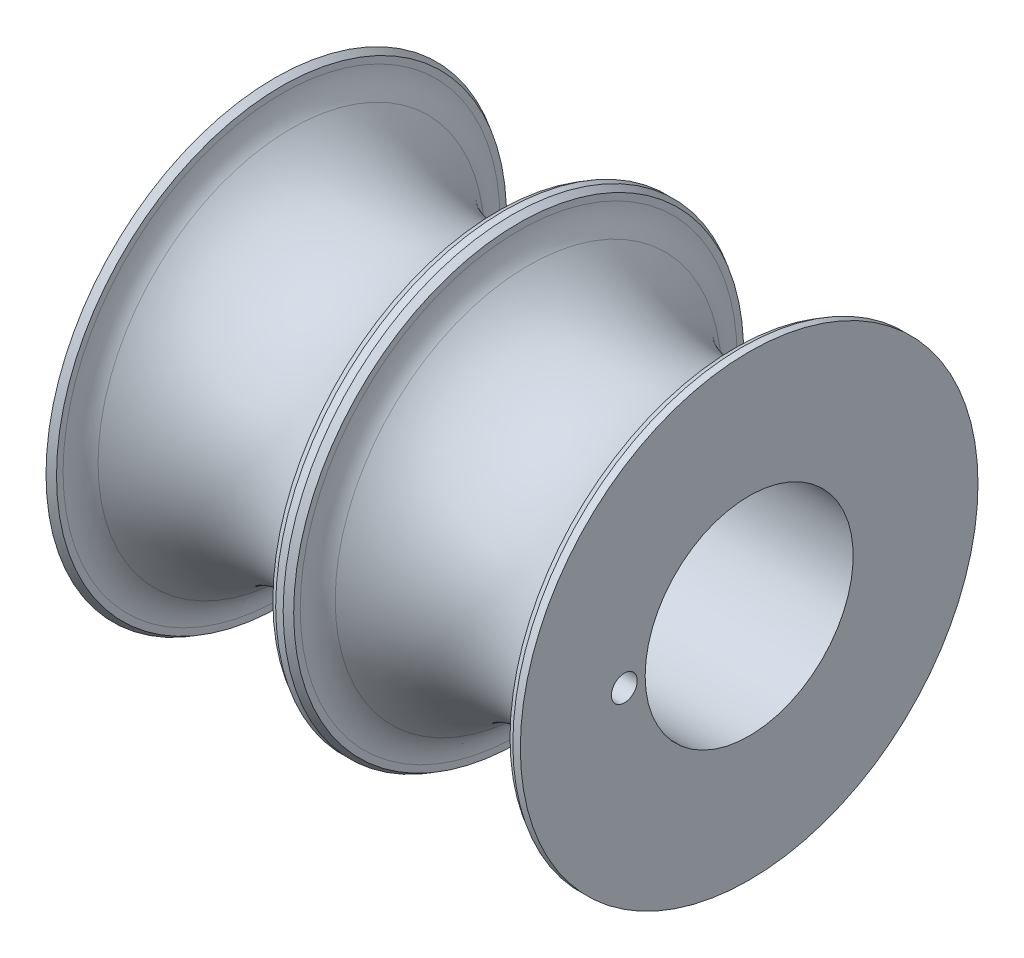
SolidWorks part; units mm, degrees
other "Detailelement1"
other "Detailelement2"
other "Detailelement3"
other "Detailelement4"
other "Detailelement5"
material "1.7131 (16MnCr5)"
ref_plane "Vorne" through (0, 0, 0) normal (0, 0, 1) x (1, 0, 0)
ref_plane "Oben" through (0, 0, 0) normal (0, 1, 0) x (1, 0, 0)
ref_plane "Rechts" through (0, 0, 0) normal (1, 0, 0) x (0, 0, -1)
ref_axis "Achse1" through (-27.8308, 0, 0) along (1, 0, 0)
sketch "Skizze1" plane through (0, 0, 0) normal (0, 0, 1) x (1, 0, 0)
  line L0 (0, 12.5) -> (57, 12.5)
  line L1 (26.8, 27.0381) -> (27.6, 27.5)
  line L2 (55.3, 27.0381) -> (56.1, 27.5)
  line L3 (29.3, 26.25) -> (29.3, 27.0381)
  line L4 (-27.8308, 0) -> (70.0749, 0) construction
  line L5 (13.8, 29.3523) -> (13.8, 13.5957) construction
  line L6 (0, 27.5) -> (0.8, 27.0381)
  line L7 (0, 27.5) -> (0, 12.5)
  line L8 (0.8, 26.25) -> (0.8, 27.0381)
  line L9 (26.8, 26.25) -> (26.8, 27.0381)
  line L10 (27.6, 27.5) -> (28.5, 27.5)
  line L11 (0, 0) -> (107.1415, 0) construction
  line L12 (28.5, 27.5) -> (29.3, 27.0381)
  line L17 (55.3, 26.25) -> (55.3, 27.0381)
  line L19 (56.1, 27.5) -> (57, 27.5)
  line L20 (57, 27.5) -> (57, 12.5)
  line L21 (42.3, 33.996) -> (42.3, 13.5957) construction
  arc A0 (41.9408, 18) -> (54.1261, 23.219) centre (42.3, 33.996) ccw
  arc A1 (55.3, 26.25) -> (54.1261, 23.219) centre (50.8, 26.25) cw
  arc A2 (29.3, 26.25) -> (30.4739, 23.219) centre (33.8, 26.25) ccw
  arc A3 (41.9408, 18) -> (30.4739, 23.219) centre (42.3, 33.996) cw
  arc A4 (0.8, 26.25) -> (1.9739, 23.219) centre (5.3, 26.25) ccw
  arc A5 (13.4408, 18) -> (1.9739, 23.219) centre (13.8, 33.996) cw
  arc A6 (13.4408, 18) -> (25.6261, 23.219) centre (13.8, 33.996) ccw
  arc A7 (26.8, 26.25) -> (25.6261, 23.219) centre (22.3, 26.25) cw
  dimension "D3" = 26
  dimension "D4" = 4.5
  dimension "D10" = 55
  dimension "D11" = 0.9
  dimension "D5" = 16
  dimension "D1" = 2
  dimension "D2" = 28.5
  dimension "D6" = 25
  dimension "D7" = 57
  dimension "D8" = 8.25
  dimension "D9" = 36
  dimension "D12" = 2.5
  dimension "D13" = 0.8
  dimension "D14" = 30
  dimension "D15" = 0.8
revolve "Rotation2" add sketch "Skizze1" angle 360 about axis through (-27.8308, 0, 0) along (1, 0, 0)
hole_wizard "Ø3.0 (3) Durchmesser Bohrung2" positions "Skizze6" profile "Skizze5" hole size "Ø3.0" standard "Gabler-Normteile"
sketch "Skizze6" plane through (0, 0, 0) normal (-1, 0, 0) x (0, 0, 1)
  point P0 (-15, 0)
  dimension "D2" = 15
sketch "Skizze5" plane through (0, 0, -15) normal (0, 1, 0) x (0, 0, 1)
  line L0 (0, 0) -> (0, 5.9013)
  line L1 (0, 5.9013) -> (1.5, 5)
  line L2 (1.5, 5) -> (1.5, 0)
  line L5 (1.5, 0) -> (0, 0)
  line L10 (0, 5.9013) -> (-1.5, 5) construction
  line L11 (0, -6.35) -> (0, 107.95) construction
  dimension "Bohrerdurchmesser" = 3
  dimension "Bohrungstiefe" = 5
  dimension "Spitzenwinkel" = 118
hole_wizard "Ø3.1 (3.1) Durchmesser Bohrung2" positions "Skizze8" profile "Skizze7" hole size "Ø3.1" standard "Gabler-Normteile"
sketch "Skizze8" plane through (57, 0, 0) normal (1, 0, 0) x (0, 0, -1)
  point P0 (-15, 0)
  dimension "D1" = 15
sketch "Skizze7" plane through (57, 0, 15) normal (0, 1, 0) x (0, 0, -1)
  line L0 (0, 0) -> (0, 5.9313)
  line L1 (0, 5.9313) -> (1.55, 5)
  line L2 (1.55, 5) -> (1.55, 0)
  line L5 (1.55, 0) -> (0, 0)
  line L10 (0, 5.9313) -> (-1.55, 5) construction
  line L11 (0, -6.35) -> (0, 107.95) construction
  dimension "Bohrerdurchmesser" = 3.1
  dimension "Bohrungstiefe" = 5
  dimension "Spitzenwinkel" = 118
